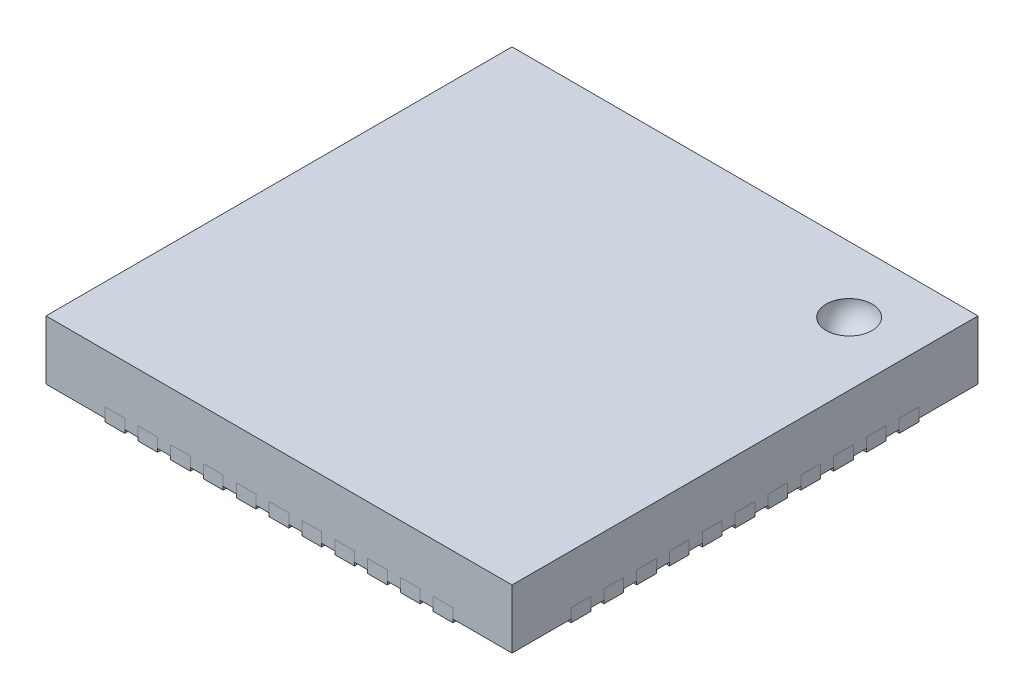
SolidWorks part; units mm, degrees
ref_plane "Alzado" through (0, 0, 0) normal (0, 0, 1) x (1, 0, 0)
ref_plane "Planta" through (0, 0, 0) normal (0, 1, 0) x (1, 0, 0)
ref_plane "Vista lateral" through (0, 0, 0) normal (1, 0, 0) x (0, 0, -1)
sketch "Croquis1" plane through (0, 0, 0) normal (0, 1, 0) x (1, 0, 0)
  line L1 (0, 0) -> (7.1, 0)
  line L2 (0, 0) -> (0, 7.1)
  line L3 (0, 7.1) -> (7.1, 7.1)
  line L4 (7.1, 0) -> (7.1, 7.1)
  dimension "D1" = 7.1
  dimension "D2" = 7.1
extrude "Extruir1" add sketch "Croquis1" along normal blind 1
sketch "Croquis2" plane through (0, 0, 0) normal (0, 0, 1) x (1, 0, 0)
  line L0 (7.1, 1) -> (7.1, 0) construction
  line L1 (0, 0) -> (7.1, 0)
  line L2 (0, 0) -> (0, 0.1)
  line L3 (0, 0.1) -> (7.1, 0.1)
  line L4 (7.1, 0) -> (7.1, 0.1)
  dimension "D1" = 0.1
extrude "Extruir2" cut sketch "Croquis2" against normal up to next
sketch "Croquis3" plane through (0, 0.1, 0) normal (0, -1, 0) x (1, 0, 0)
  line L0 (3.55, 0) -> (3.55, -7.1) construction
  line L1 (7.1, 0) -> (0, 0) construction
  line L2 (0, -7.1) -> (7.1, -7.1) construction
  line L3 (3.7, 0) -> (3.4, 0)
  line L4 (5.95, -0.85) -> (1.15, -0.85)
  line L5 (6.25, -1.15) -> (6.25, -5.95)
  line L6 (5.95, -6.25) -> (1.15, -6.25)
  line L7 (0.85, -1.15) -> (0.85, -5.95)
  line L8 (6.25, -0.85) -> (0.85, -6.25) construction
  line L9 (6.25, -6.25) -> (0.85, -0.85) construction
  line L10 (3.4, 0) -> (3.4, -0.54)
  line L11 (2.9, 0) -> (3.2, 0)
  line L12 (2.4, 0) -> (2.7, 0)
  line L13 (3.2, 0) -> (3.2, -0.54)
  line L14 (2.7, 0) -> (2.7, -0.54)
  line L15 (2.9, 0) -> (2.9, -0.54)
  line L16 (2.4, 0) -> (2.4, -0.54)
  line L17 (1.9, 0) -> (2.2, 0)
  line L18 (2.2, 0) -> (2.2, -0.54)
  line L19 (1.9, 0) -> (1.9, -0.54)
  line L20 (1.4, 0) -> (1.7, 0)
  line L21 (1.7, 0) -> (1.7, -0.54)
  line L22 (1.4, 0) -> (1.4, -0.54)
  line L23 (0.9, 0) -> (1.2, 0)
  line L24 (1.2, 0) -> (1.2, -0.54)
  line L25 (0.9, 0) -> (0.9, -0.54)
  line L26 (6.2, 0) -> (6.2, -0.54)
  line L27 (5.9, 0) -> (5.9, -0.54)
  line L28 (6.2, 0) -> (5.9, 0)
  line L29 (5.7, 0) -> (5.7, -0.54)
  line L30 (5.4, 0) -> (5.4, -0.54)
  line L31 (5.7, 0) -> (5.4, 0)
  line L32 (5.2, 0) -> (5.2, -0.54)
  line L33 (4.9, 0) -> (4.9, -0.54)
  line L34 (5.2, 0) -> (4.9, 0)
  line L35 (4.7, 0) -> (4.7, -0.54)
  line L36 (4.2, 0) -> (4.2, -0.54)
  line L37 (4.4, 0) -> (4.4, -0.54)
  line L38 (3.9, 0) -> (3.9, -0.54)
  line L39 (4.7, 0) -> (4.4, 0)
  line L40 (4.2, 0) -> (3.9, 0)
  line L41 (3.7, 0) -> (3.7, -0.54)
  line L42 (0, -3.55) -> (7.1, -3.55) construction
  line L43 (0, -7.1) -> (0, 0) construction
  line L44 (7.1, -7.1) -> (7.1, 0) construction
  line L45 (7.1, -3.7) -> (7.1, -3.4)
  line L46 (7.1, -3.4) -> (6.56, -3.4)
  line L47 (7.1, -2.9) -> (7.1, -3.2)
  line L48 (7.1, -2.4) -> (7.1, -2.7)
  line L49 (7.1, -3.2) -> (6.56, -3.2)
  line L50 (7.1, -2.7) -> (6.56, -2.7)
  line L51 (7.1, -2.9) -> (6.56, -2.9)
  line L52 (7.1, -2.4) -> (6.56, -2.4)
  line L53 (7.1, -1.9) -> (7.1, -2.2)
  line L54 (7.1, -2.2) -> (6.56, -2.2)
  line L55 (7.1, -1.9) -> (6.56, -1.9)
  line L56 (7.1, -1.4) -> (7.1, -1.7)
  line L57 (7.1, -1.7) -> (6.56, -1.7)
  line L58 (7.1, -1.4) -> (6.56, -1.4)
  line L59 (7.1, -0.9) -> (7.1, -1.2)
  line L60 (7.1, -1.2) -> (6.56, -1.2)
  line L61 (7.1, -0.9) -> (6.56, -0.9)
  line L62 (7.1, -6.2) -> (6.56, -6.2)
  line L63 (7.1, -5.9) -> (6.56, -5.9)
  line L64 (7.1, -6.2) -> (7.1, -5.9)
  line L65 (7.1, -5.7) -> (6.56, -5.7)
  line L66 (7.1, -5.4) -> (6.56, -5.4)
  line L67 (7.1, -5.7) -> (7.1, -5.4)
  line L68 (7.1, -5.2) -> (6.56, -5.2)
  line L69 (7.1, -4.9) -> (6.56, -4.9)
  line L70 (7.1, -5.2) -> (7.1, -4.9)
  line L71 (7.1, -4.7) -> (6.56, -4.7)
  line L72 (7.1, -4.2) -> (6.56, -4.2)
  line L73 (7.1, -4.4) -> (6.56, -4.4)
  line L74 (7.1, -3.9) -> (6.56, -3.9)
  line L75 (7.1, -4.7) -> (7.1, -4.4)
  line L76 (7.1, -4.2) -> (7.1, -3.9)
  line L77 (7.1, -3.7) -> (6.56, -3.7)
  line L78 (3.4, -7.1) -> (3.7, -7.1)
  line L79 (3.7, -7.1) -> (3.7, -6.56)
  line L80 (4.2, -7.1) -> (3.9, -7.1)
  line L81 (4.7, -7.1) -> (4.4, -7.1)
  line L82 (3.9, -7.1) -> (3.9, -6.56)
  line L83 (4.4, -7.1) -> (4.4, -6.56)
  line L84 (4.2, -7.1) -> (4.2, -6.56)
  line L85 (4.7, -7.1) -> (4.7, -6.56)
  line L86 (5.2, -7.1) -> (4.9, -7.1)
  line L87 (4.9, -7.1) -> (4.9, -6.56)
  line L88 (5.2, -7.1) -> (5.2, -6.56)
  line L89 (5.7, -7.1) -> (5.4, -7.1)
  line L90 (5.4, -7.1) -> (5.4, -6.56)
  line L91 (5.7, -7.1) -> (5.7, -6.56)
  line L92 (6.2, -7.1) -> (5.9, -7.1)
  line L93 (5.9, -7.1) -> (5.9, -6.56)
  line L94 (6.2, -7.1) -> (6.2, -6.56)
  line L95 (0.9, -7.1) -> (0.9, -6.56)
  line L96 (1.2, -7.1) -> (1.2, -6.56)
  line L97 (0.9, -7.1) -> (1.2, -7.1)
  line L98 (1.4, -7.1) -> (1.4, -6.56)
  line L99 (1.7, -7.1) -> (1.7, -6.56)
  line L100 (1.4, -7.1) -> (1.7, -7.1)
  line L101 (1.9, -7.1) -> (1.9, -6.56)
  line L102 (2.2, -7.1) -> (2.2, -6.56)
  line L103 (1.9, -7.1) -> (2.2, -7.1)
  line L104 (2.4, -7.1) -> (2.4, -6.56)
  line L105 (2.9, -7.1) -> (2.9, -6.56)
  line L106 (2.7, -7.1) -> (2.7, -6.56)
  line L107 (3.2, -7.1) -> (3.2, -6.56)
  line L108 (2.4, -7.1) -> (2.7, -7.1)
  line L109 (2.9, -7.1) -> (3.2, -7.1)
  line L110 (3.4, -7.1) -> (3.4, -6.56)
  line L111 (0, -3.4) -> (0, -3.7)
  line L112 (0, -3.7) -> (0.54, -3.7)
  line L113 (0, -4.2) -> (0, -3.9)
  line L114 (0, -4.7) -> (0, -4.4)
  line L115 (0, -3.9) -> (0.54, -3.9)
  line L116 (0, -4.4) -> (0.54, -4.4)
  line L117 (0, -4.2) -> (0.54, -4.2)
  line L118 (0, -4.7) -> (0.54, -4.7)
  line L119 (0, -5.2) -> (0, -4.9)
  line L120 (0, -4.9) -> (0.54, -4.9)
  line L121 (0, -5.2) -> (0.54, -5.2)
  line L122 (0, -5.7) -> (0, -5.4)
  line L123 (0, -5.4) -> (0.54, -5.4)
  line L124 (0, -5.7) -> (0.54, -5.7)
  line L125 (0, -6.2) -> (0, -5.9)
  line L126 (0, -5.9) -> (0.54, -5.9)
  line L127 (0, -6.2) -> (0.54, -6.2)
  line L128 (0, -0.9) -> (0.54, -0.9)
  line L129 (0, -1.2) -> (0.54, -1.2)
  line L130 (0, -0.9) -> (0, -1.2)
  line L131 (0, -1.4) -> (0.54, -1.4)
  line L132 (0, -1.7) -> (0.54, -1.7)
  line L133 (0, -1.4) -> (0, -1.7)
  line L134 (0, -1.9) -> (0.54, -1.9)
  line L135 (0, -2.2) -> (0.54, -2.2)
  line L136 (0, -1.9) -> (0, -2.2)
  line L137 (0, -2.4) -> (0.54, -2.4)
  line L138 (0, -2.9) -> (0.54, -2.9)
  line L139 (0, -2.7) -> (0.54, -2.7)
  line L140 (0, -3.2) -> (0.54, -3.2)
  line L141 (0, -2.4) -> (0, -2.7)
  line L142 (0, -2.9) -> (0, -3.2)
  line L143 (0, -3.4) -> (0.54, -3.4)
  arc A0 (1.15, -0.85) -> (0.85, -1.15) centre (1.15, -1.15) ccw
  arc A1 (5.95, -0.85) -> (6.25, -1.15) centre (5.95, -1.15) cw
  arc A2 (6.25, -5.95) -> (5.95, -6.25) centre (5.95, -5.95) cw
  arc A3 (1.15, -6.25) -> (0.85, -5.95) centre (1.15, -5.95) cw
  arc A4 (3.4, -0.54) -> (3.7, -0.54) centre (3.55, -0.54) ccw
  arc A5 (3.2, -0.54) -> (2.9, -0.54) centre (3.05, -0.54) cw
  arc A6 (2.7, -0.54) -> (2.4, -0.54) centre (2.55, -0.54) cw
  arc A7 (2.2, -0.54) -> (1.9, -0.54) centre (2.05, -0.54) cw
  arc A8 (1.7, -0.54) -> (1.4, -0.54) centre (1.55, -0.54) cw
  arc A9 (1.2, -0.54) -> (0.9, -0.54) centre (1.05, -0.54) cw
  arc A10 (5.9, -0.54) -> (6.2, -0.54) centre (6.05, -0.54) ccw
  arc A11 (5.4, -0.54) -> (5.7, -0.54) centre (5.55, -0.54) ccw
  arc A12 (4.9, -0.54) -> (5.2, -0.54) centre (5.05, -0.54) ccw
  arc A13 (4.4, -0.54) -> (4.7, -0.54) centre (4.55, -0.54) ccw
  arc A14 (3.9, -0.54) -> (4.2, -0.54) centre (4.05, -0.54) ccw
  arc A15 (6.56, -3.4) -> (6.56, -3.7) centre (6.56, -3.55) ccw
  arc A16 (6.56, -3.2) -> (6.56, -2.9) centre (6.56, -3.05) cw
  arc A17 (6.56, -2.7) -> (6.56, -2.4) centre (6.56, -2.55) cw
  arc A18 (6.56, -2.2) -> (6.56, -1.9) centre (6.56, -2.05) cw
  arc A19 (6.56, -1.7) -> (6.56, -1.4) centre (6.56, -1.55) cw
  arc A20 (6.56, -1.2) -> (6.56, -0.9) centre (6.56, -1.05) cw
  arc A21 (6.56, -5.9) -> (6.56, -6.2) centre (6.56, -6.05) ccw
  arc A22 (6.56, -5.4) -> (6.56, -5.7) centre (6.56, -5.55) ccw
  arc A23 (6.56, -4.9) -> (6.56, -5.2) centre (6.56, -5.05) ccw
  arc A24 (6.56, -4.4) -> (6.56, -4.7) centre (6.56, -4.55) ccw
  arc A25 (6.56, -3.9) -> (6.56, -4.2) centre (6.56, -4.05) ccw
  arc A26 (3.7, -6.56) -> (3.4, -6.56) centre (3.55, -6.56) ccw
  arc A27 (3.9, -6.56) -> (4.2, -6.56) centre (4.05, -6.56) cw
  arc A28 (4.4, -6.56) -> (4.7, -6.56) centre (4.55, -6.56) cw
  arc A29 (4.9, -6.56) -> (5.2, -6.56) centre (5.05, -6.56) cw
  arc A30 (5.4, -6.56) -> (5.7, -6.56) centre (5.55, -6.56) cw
  arc A31 (5.9, -6.56) -> (6.2, -6.56) centre (6.05, -6.56) cw
  arc A32 (1.2, -6.56) -> (0.9, -6.56) centre (1.05, -6.56) ccw
  arc A33 (1.7, -6.56) -> (1.4, -6.56) centre (1.55, -6.56) ccw
  arc A34 (2.2, -6.56) -> (1.9, -6.56) centre (2.05, -6.56) ccw
  arc A35 (2.7, -6.56) -> (2.4, -6.56) centre (2.55, -6.56) ccw
  arc A36 (3.2, -6.56) -> (2.9, -6.56) centre (3.05, -6.56) ccw
  arc A37 (0.54, -3.7) -> (0.54, -3.4) centre (0.54, -3.55) ccw
  arc A38 (0.54, -3.9) -> (0.54, -4.2) centre (0.54, -4.05) cw
  arc A39 (0.54, -4.4) -> (0.54, -4.7) centre (0.54, -4.55) cw
  arc A40 (0.54, -4.9) -> (0.54, -5.2) centre (0.54, -5.05) cw
  arc A41 (0.54, -5.4) -> (0.54, -5.7) centre (0.54, -5.55) cw
  arc A42 (0.54, -5.9) -> (0.54, -6.2) centre (0.54, -6.05) cw
  arc A43 (0.54, -1.2) -> (0.54, -0.9) centre (0.54, -1.05) ccw
  arc A44 (0.54, -1.7) -> (0.54, -1.4) centre (0.54, -1.55) ccw
  arc A45 (0.54, -2.2) -> (0.54, -1.9) centre (0.54, -2.05) ccw
  arc A46 (0.54, -2.7) -> (0.54, -2.4) centre (0.54, -2.55) ccw
  arc A47 (0.54, -3.2) -> (0.54, -2.9) centre (0.54, -3.05) ccw
  point P6 (3.55, -3.55)
  point P27 (3.05, -0.27)
  point P35 (2.55, -0.27)
  point P41 (2.05, -0.27)
  point P47 (1.55, -0.27)
  point P53 (1.05, -0.27)
  point P83 (6.05, -0.27)
  point P84 (5.55, -0.27)
  point P85 (5.05, -0.27)
  point P86 (4.55, -0.27)
  point P87 (4.05, -0.27)
  point P101 (6.83, -3.05)
  point P109 (6.83, -2.55)
  point P115 (6.83, -2.05)
  point P121 (6.83, -1.55)
  point P127 (6.83, -1.05)
  point P157 (6.83, -6.05)
  point P158 (6.83, -5.55)
  point P159 (6.83, -5.05)
  point P160 (6.83, -4.55)
  point P161 (6.83, -4.05)
  point P166 (4.05, -6.83)
  point P174 (4.55, -6.83)
  point P180 (5.05, -6.83)
  point P186 (5.55, -6.83)
  point P192 (6.05, -6.83)
  point P222 (1.05, -6.83)
  point P223 (1.55, -6.83)
  point P224 (2.05, -6.83)
  point P225 (2.55, -6.83)
  point P226 (3.05, -6.83)
  point P231 (0.27, -4.05)
  point P239 (0.27, -4.55)
  point P245 (0.27, -5.05)
  point P251 (0.27, -5.55)
  point P257 (0.27, -6.05)
  point P287 (0.27, -1.05)
  point P288 (0.27, -1.55)
  point P289 (0.27, -2.05)
  point P290 (0.27, -2.55)
  point P291 (0.27, -3.05)
  dimension "D3" = 0.3
  dimension "D1" = 5.4
  dimension "D2" = 5.4
  dimension "D4" = 0.15
  dimension "D5" = 0.54
  dimension "D6" = 0.3
  dimension "D7" = 0.5
extrude "Extruir3" cut sketch "Croquis3" against normal blind 0.15
sketch "Croquis8" plane through (0, 0.25, 0) normal (0, -1, 0) x (1, 0, 0)
  line L0 (0, -6.2) -> (0.54, -6.2) construction
  line L1 (0.54, -5.9) -> (0, -5.9) construction
  line L2 (0, -5.9) -> (0, -6.2) construction
  line L3 (0, -6.2) -> (0.54, -6.2)
  line L4 (0.54, -5.9) -> (0, -5.9)
  line L5 (0, -5.9) -> (0, -6.2)
  arc A0 (0.54, -6.2) -> (0.54, -5.9) centre (0.54, -6.05) ccw construction
  arc A1 (0.54, -6.2) -> (0.54, -5.9) centre (0.54, -6.05) ccw
extrude "Extruir5" add sketch "Croquis8" along normal blind 0.2 separate body
pattern_linear "MatrizL1" count 11 spacing 0.5 along (0, 0, 1) of bodies 105
sketch "Croquis9" plane through (0, 0.25, 0) normal (0, -1, 0) x (1, 0, 0)
  line L0 (0.9, 0) -> (0.9, -0.54) construction
  line L1 (1.2, 0) -> (0.9, 0) construction
  line L2 (1.2, -0.54) -> (1.2, 0) construction
  line L3 (0.9, 0) -> (0.9, -0.54)
  line L4 (1.2, 0) -> (0.9, 0)
  line L5 (1.2, -0.54) -> (1.2, 0)
  arc A0 (0.9, -0.54) -> (1.2, -0.54) centre (1.05, -0.54) ccw construction
  arc A1 (0.9, -0.54) -> (1.2, -0.54) centre (1.05, -0.54) ccw
extrude "Extruir6" add sketch "Croquis9" along normal blind 0.2 separate body
pattern_linear "MatrizL2" count 11 spacing 0.5 along (1, 0, 0) of bodies 116
ref_plane "Plano2" through (0.85, 0.1, -3.55) normal (0, 0, -1) x (-1, 0, 0)
ref_plane "Plano3" through (3.55, 0.1, -0.85) normal (-1, 0, 0) x (0, 0, 1)
mirror "Simetría1" about plane through (3.55, 0.1, -0.85) normal (-1, 0, 0) of bodies 115 114 113 112 111 110 109 108 107 106 105
mirror "Simetría2" about plane through (0.85, 0.1, -3.55) normal (0, 0, -1) of bodies 116 117 118 119 120 121 122 123 124 125 126
sketch "Croquis10" plane through (0, 1, 0) normal (0, 1, 0) x (1, 0, 0)
  line L0 (7.1, 6.1) -> (6.1, 6.1) construction
  line L1 (7.1, 0) -> (7.1, 7.1) construction
  line L2 (6.1, 6.1) -> (6.1, 7.1) construction
  line L3 (7.1, 7.1) -> (0, 7.1) construction
  line L4 (6.4867, 6.1) -> (5.7867, 6.1)
  arc A0 (6.4867, 6.1) -> (5.7867, 6.1) centre (6.1367, 6.1) ccw
  dimension "D3" = 0.7
  dimension "D1" = 1
  dimension "D2" = 1
revolve "Cortar-Revolución1" cut sketch "Croquis10" angle 360 about L4
sketch "Croquis11" plane through (0, 0.25, 0) normal (0, -1, 0) x (1, 0, 0)
  line L4 (0.85, -1.15) -> (0.85, -5.95)
  line L5 (1.15, -6.25) -> (5.95, -6.25)
  line L6 (6.25, -5.95) -> (6.25, -1.15)
  line L7 (5.95, -0.85) -> (1.15, -0.85)
  line L8 (0.85, -1.15) -> (0.85, -5.95)
  line L9 (1.15, -6.25) -> (5.95, -6.25)
  line L10 (6.25, -5.95) -> (6.25, -1.15)
  line L11 (5.95, -0.85) -> (1.15, -0.85)
  arc A4 (1.15, -0.85) -> (0.85, -1.15) centre (1.15, -1.15) ccw
  arc A5 (0.85, -5.95) -> (1.15, -6.25) centre (1.15, -5.95) ccw
  arc A6 (5.95, -6.25) -> (6.25, -5.95) centre (5.95, -5.95) ccw
  arc A7 (6.25, -1.15) -> (5.95, -0.85) centre (5.95, -1.15) ccw
  arc A8 (1.15, -0.85) -> (0.85, -1.15) centre (1.15, -1.15) ccw
  arc A9 (0.85, -5.95) -> (1.15, -6.25) centre (1.15, -5.95) ccw
  arc A10 (5.95, -6.25) -> (6.25, -5.95) centre (5.95, -5.95) ccw
  arc A11 (6.25, -1.15) -> (5.95, -0.85) centre (5.95, -1.15) ccw
  dimension "D1" = 0
extrude "Extruir8" add sketch "Croquis11" along normal blind 0.2
